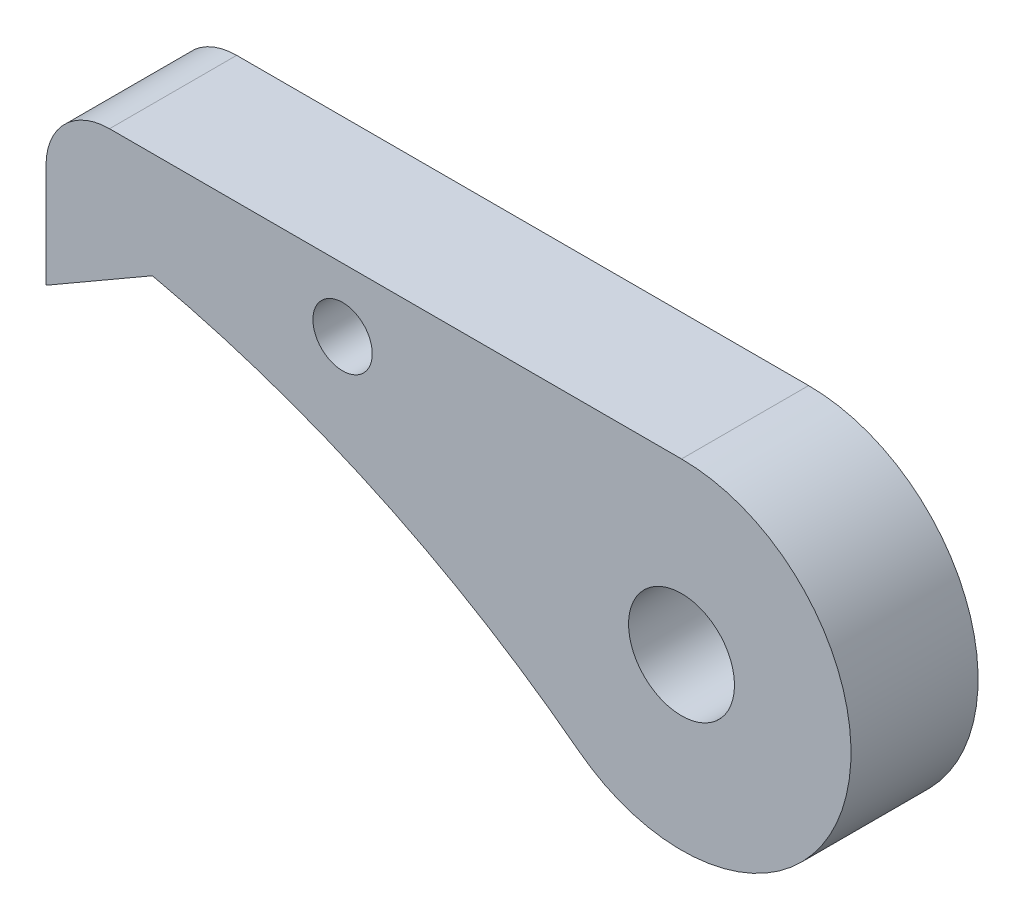
SolidWorks part; units mm, degrees
material "AISI 1045 Steel, cold drawn"
ref_plane "Front" through (0, 0, 0) normal (0, 0, 1) x (1, 0, 0)
ref_plane "Top" through (0, 0, 0) normal (0, 1, 0) x (1, 0, 0)
ref_plane "Right" through (0, 0, 0) normal (1, 0, 0) x (0, 0, -1)
sketch "Sketch1" plane through (0, 0, 0) normal (0, 0, 1) x (1, 0, 0)
  line L0 (0, 8) -> (-27, 8)
  line L1 (-30, 5) -> (-30, 0.1)
  line L2 (-30, 0.1) -> (-24.9771, 3)
  circle A0 centre (0, 0) radius 2.5
  arc A1 (-4.8536, -6.3595) -> (0, 8) centre (0, 0) ccw
  arc A2 (-24.9771, 3) -> (-4.8536, -6.3595) centre (-36.1859, -47.413) cw
  arc A3 (-27, 8) -> (-30, 5) centre (-27, 5) ccw
  point P8 (8, 0)
  dimension "D1" = 5
  dimension "D2" = 8
  dimension "D6" = 3
  dimension "D7" = 5
  dimension "D8" = 7.9
  dimension "D9" = 51.6441
  dimension "D3" = 60
  dimension "D4" = 38
  dimension "D5" = 30
extrude "Boss-Extrude1" add sketch "Sketch1" along normal mid plane 6
sketch "Sketch2" plane through (0, 0, 3) normal (0, 0, 1) x (1, 0, 0)
  line L0 (-30, 5) -> (6.245, 5) construction
  line L1 (-30, 5) -> (-30, 0.1) construction
  arc A0 (-4.8536, -6.3595) -> (0, 8) centre (0, 0) ccw construction
  circle A1 centre (-16, 5) radius 1.4
  dimension "D1" = 2.8
  dimension "D2" = 14
extrude "Cut-Extrude1" cut sketch "Sketch2" against normal blind 10
